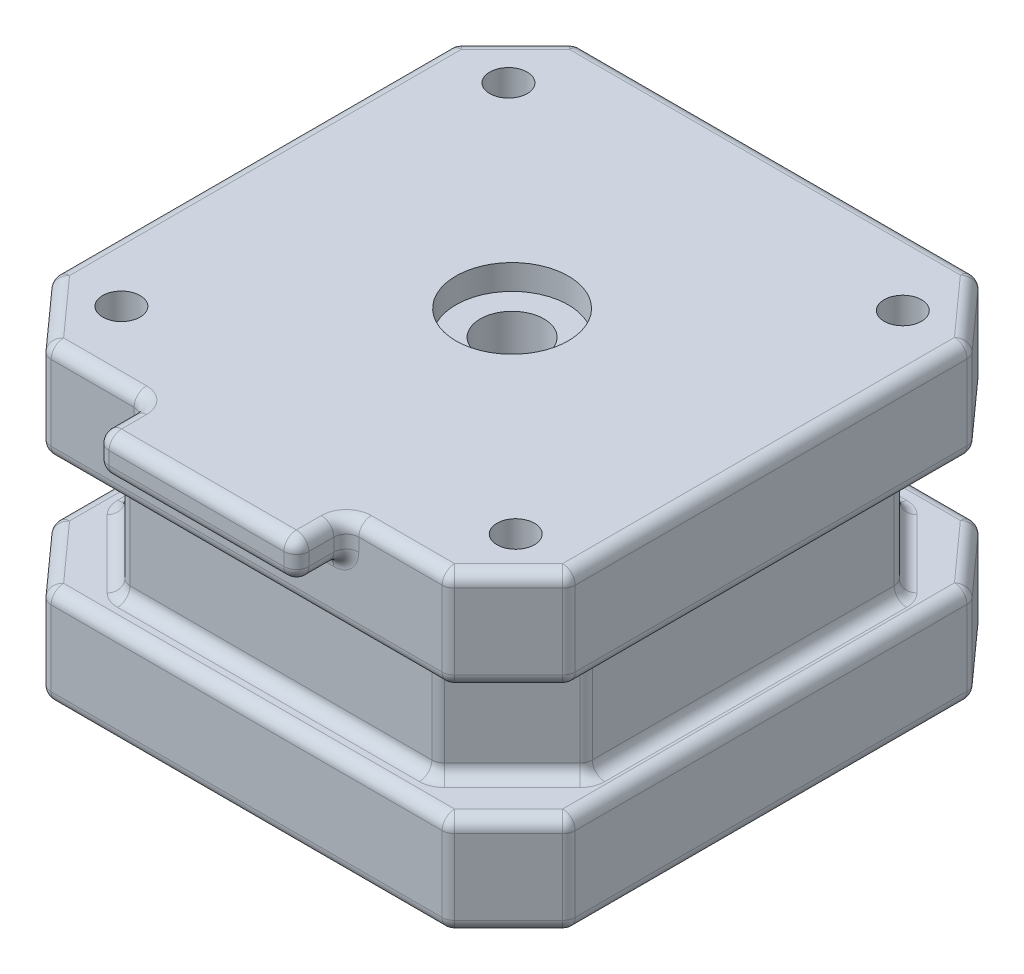
SolidWorks part; units mm, degrees
ref_plane "Front Plane" through (0, 0, 0) normal (0, 0, 1) x (1, 0, 0)
ref_plane "Top Plane" through (0, 0, 0) normal (0, 1, 0) x (1, 0, 0)
ref_plane "Right Plane" through (0, 0, 0) normal (1, 0, 0) x (0, 0, -1)
sketch "Sketch1" plane through (0, 0, 0) normal (0, 1, 0) x (1, 0, 0)
  line L0 (16.085, 21.2606) -> (-16.085, 21.2606)
  line L1 (-16.085, 21.2606) -> (-20.9994, 16.3462)
  line L2 (-20.9994, 16.3462) -> (-20.9994, -15.8238)
  line L3 (-20.9994, -15.8238) -> (-16.3609, -20.9994)
  line L4 (-16.3609, -20.9994) -> (15.8091, -20.9994)
  line L5 (15.8091, -20.9994) -> (20.7235, -16.085)
  line L6 (20.7235, -16.085) -> (20.7235, 16.085)
  line L7 (20.7235, 16.085) -> (16.085, 21.2606)
  point P2 (0, 21.2606)
  point P9 (20.7235, 0)
  dimension "D1" = 6.95
  dimension "D2" = 6.95
  dimension "D3" = 32.17
  dimension "D4" = 32.17
extrude "Boss-Extrude1" add sketch "Sketch1" along normal blind 8.02
sketch "Sketch2" plane through (0, 0, 0) normal (0, -1, 0) x (1, 0, 0)
  line L0 (-15.79, 15.5) -> (15.79, 15.5) construction
  line L1 (15.79, 15.5) -> (15.79, -15.5) construction
  circle A0 centre (-15.79, 15.5) radius 1.5
  circle A1 centre (15.79, 15.5) radius 1.5
  circle A2 centre (-15.79, -15.5) radius 1.5
  circle A3 centre (15.79, -15.5) radius 1.5
  point P8 (0, 15.5)
  point P9 (15.79, 0)
  dimension "D1" = 3
  dimension "D2" = 31.58
  dimension "D3" = 31
extrude "Cut-Extrude1" cut sketch "Sketch2" against normal blind 6
sketch "Sketch3" plane through (0, 0, 0) normal (0, -1, 0) x (1, 0, 0)
  circle A0 centre (0, 0) radius 11
  circle A1 centre (0, 0) radius 4.5
  dimension "D1" = 22
  dimension "D2" = 9
extrude "Boss-Extrude2" add sketch "Sketch3" along normal blind 2
sketch "Sketch5" plane through (0, 8.02, 0) normal (0, 1, 0) x (1, 0, 0)
  line L0 (-18.5104, 12.5) -> (-12.5, 18.5104)
  line L1 (-12.5, 18.5104) -> (12.5, 18.5104)
  line L2 (12.5, 18.5104) -> (18.5104, 12.5)
  line L3 (18.5104, 12.5) -> (18.5104, -12.5)
  line L4 (18.5104, -12.5) -> (12.5, -18.5104)
  line L5 (12.5, -18.5104) -> (-12.5, -18.5104)
  line L6 (-12.5, -18.5104) -> (-18.5104, -12.5)
  line L7 (-18.5104, -12.5) -> (-18.5104, 12.5)
  point P6 (0, 18.5104)
  point P9 (-18.5104, 0)
  dimension "D1" = 25
  dimension "D2" = 25
  dimension "D3" = 8.5
  dimension "D4" = 8.5
extrude "Boss-Extrude3" add sketch "Sketch5" along normal blind 9
ref_plane "Plane1" through (0, 12.52, 0) normal (0, -1, 0) x (-1, 0, 0)
mirror "Mirror1" about plane through (0, 12.52, 0) normal (0, -1, 0) of "Boss-Extrude1", "Cut-Extrude1"
sketch "Sketch4" plane through (0, 0, 0) normal (0, -1, 0) x (1, 0, 0)
  circle A0 centre (0, 0) radius 2.55
  dimension "D1" = 5.1
extrude "Cut-Extrude2" cut sketch "Sketch4" against normal through all
sketch "Sketch6" plane through (0, 25.04, 0) normal (0, 1, 0) x (1, 0, 0)
  circle A0 centre (0, 0) radius 4.5
  dimension "D1" = 9
extrude "Cut-Extrude3" cut sketch "Sketch6" against normal blind 2
sketch "Sketch8" plane through (0, 25.04, 0) normal (0, 1, 0) x (1, 0, 0)
  line L0 (-16.3609, -20.9994) -> (15.8091, -20.9994) construction
  line L1 (-8.2759, -20.9994) -> (7.7241, -20.9994)
  line L2 (-8.2759, -20.9994) -> (-8.2759, -24.9994)
  line L3 (-8.2759, -24.9994) -> (7.7241, -24.9994)
  line L4 (7.7241, -20.9994) -> (7.7241, -24.9994)
  line L5 (-16.3609, -20.9994) -> (15.8091, -20.9994)
  point P6 (-0.2759, -20.9994)
  point P7 (-0.2759, -20.9994)
  line M16 (-16.3609, -20.9994) -> (15.8091, -20.9994)
  dimension "D1" = 4
  dimension "D2" = 16
extrude "Boss-Extrude5" add sketch "Sketch8" against normal blind 3.04 contours L4 L2 L3 M16
fillet "Fillet1" radius 1 84 edges at (7.7241, 23.52, 20.9994) (7.7241, 23.52, 24.9994) (-8.2759, 23.52, 24.9994) (-8.2759, 23.52, 20.9994) (-0.2759, 22, 20.9994) (-8.2759, 22, 22.9994) (-0.2759, 22, 24.9994) (7.7241, 22, 22.9994) (12.5, 12.52, -18.5104) (-12.5, 12.52, -18.5104) (-18.5104, 12.52, -12.5) (18.5104, 12.52, -12.5) (-18.5104, 12.52, 12.5) (18.5104, 12.52, 12.5) (-12.5, 12.52, 18.5104) (12.5, 12.52, 18.5104) (-16.085, 4.01, -21.2606) (-20.9994, 4.01, -16.3462) (-20.9994, 21.03, -16.3462) (-16.085, 21.03, -21.2606) (-16.3609, 21.03, 20.9994) (-20.9994, 21.03, 15.8238) (20.7235, 21.03, 16.085) (15.8091, 21.03, 20.9994) (16.085, 21.03, -21.2606) (20.7235, 21.03, -16.085) (20.7235, 4.01, -16.085) (16.085, 4.01, -21.2606) (20.7235, 4.01, 16.085) (-16.3609, 4.01, 20.9994) (15.8091, 4.01, 20.9994) (20.7235, 8.02, 0) (18.2663, 8.02, 18.5422) (-0.2759, 8.02, 20.9994) (-18.6801, 8.02, 18.4116) (-20.9994, 8.02, -0.2612) (-18.5422, 8.02, -18.8034) (0, 8.02, -21.2606) (18.4043, 8.02, -18.6728) (-15.5052, 8.02, 15.5052) (0, 8.02, 18.5104) (15.5052, 8.02, 15.5052) (18.5104, 8.02, 0) (15.5052, 8.02, -15.5052) (0, 8.02, -18.5104) (-15.5052, 8.02, -15.5052) (-18.5104, 8.02, 0) (0, 0, -21.2606) (-18.5422, 0, -18.8034) (-20.9994, 0, -0.2612) (-18.6801, 0, 18.4116) (-0.2759, 0, 20.9994) (18.2663, 0, 18.5422) (20.7235, 0, 0) (18.4043, 0, -18.6728) (0, 17.02, -21.2606) (-18.5422, 17.02, -18.8034) (-20.9994, 17.02, -0.2612) (-18.6801, 17.02, 18.4116) (-0.2759, 17.02, 20.9994) (18.2663, 17.02, 18.5422) (20.7235, 17.02, 0) (18.4043, 17.02, -18.6728) (0, 17.02, -18.5104) (15.5052, 17.02, -15.5052) (18.5104, 17.02, 0) (15.5052, 17.02, 15.5052) (0, 17.02, 18.5104) (-15.5052, 17.02, 15.5052) (-18.5104, 17.02, 0) (-15.5052, 17.02, -15.5052) (20.7235, 25.04, 0) (18.2663, 25.04, 18.5422) (11.7666, 25.04, 20.9994) (7.7241, 25.04, 22.9994) (-0.2759, 25.04, 24.9994) (-8.2759, 25.04, 22.9994) (-12.3184, 25.04, 20.9994) (-18.6801, 25.04, 18.4116) (-20.9994, 25.04, -0.2612) (-18.5422, 25.04, -18.8034) (0, 25.04, -21.2606) (18.4043, 25.04, -18.6728) (-20.9994, 4.01, 15.8238)
